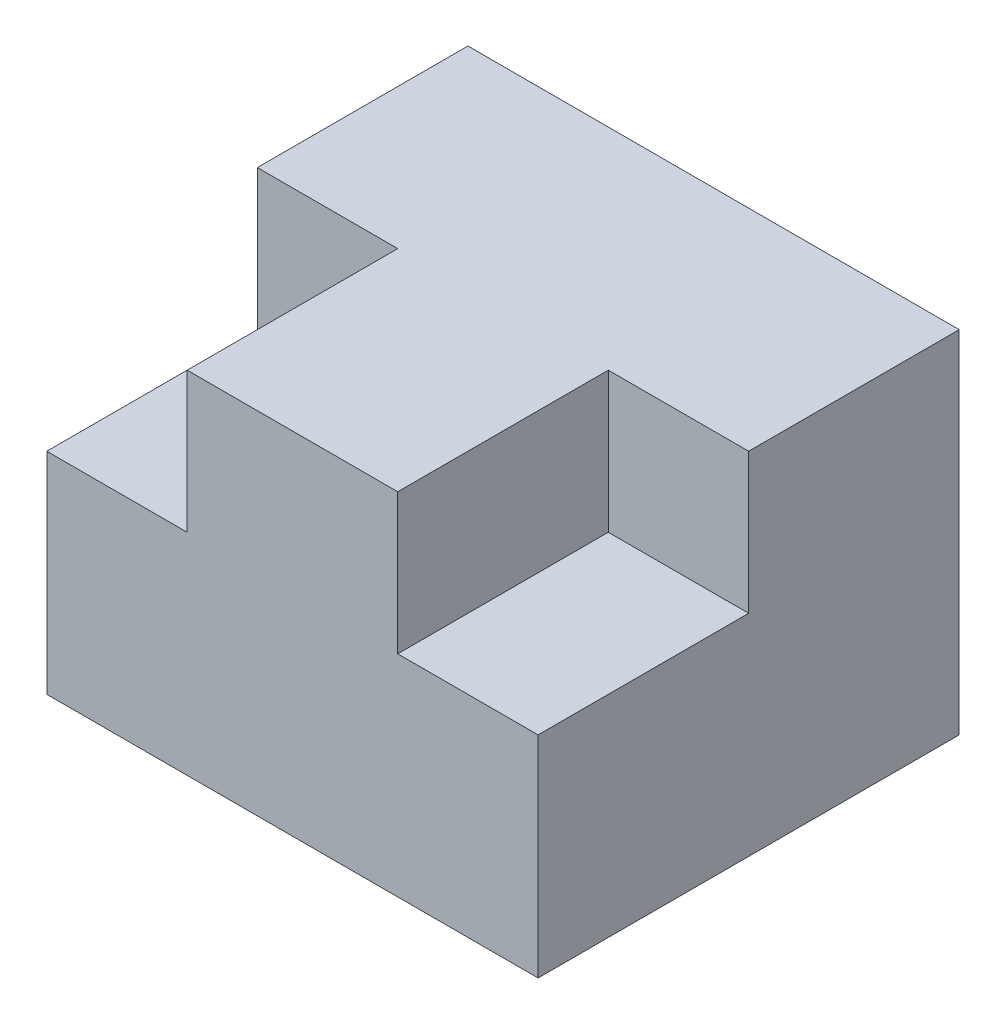
SolidWorks part; units mm, degrees
ref_plane "Front Plane" through (0, 0, 0) normal (0, 0, 1) x (1, 0, 0)
ref_plane "Top Plane" through (0, 0, 0) normal (0, 1, 0) x (1, 0, 0)
ref_plane "Right Plane" through (0, 0, 0) normal (1, 0, 0) x (0, 0, -1)
sketch "Sketch1" plane through (0, 0, 0) normal (0, 0, 1) x (1, 0, 0)
  line L0 (-17.5, 0) -> (17.5, 0)
  line L1 (17.5, 0) -> (17.5, 15)
  line L2 (17.5, 15) -> (7.5, 15)
  line L3 (7.5, 15) -> (7.5, 25)
  line L4 (7.5, 25) -> (-7.5, 25)
  line L5 (-7.5, 25) -> (-7.5, 15)
  line L6 (-7.5, 15) -> (-17.5, 15)
  line L7 (-17.5, 15) -> (-17.5, 0)
  point P4 (0, 0)
  dimension "D1" = 15
  dimension "35" = 35
  dimension "D2" = 10
  dimension "D3" = 10
  dimension "D4" = 10
  dimension "D5" = 10
extrude "Boss-Extrude1" add sketch "Sketch1" along normal blind 15
sketch "Sketch2" plane through (0, 0, 0) normal (0, 0, -1) x (-1, 0, 0)
  line L1 (-17.5, 0) -> (17.5, 0)
  line L2 (-17.5, 0) -> (-17.5, 25)
  line L3 (-17.5, 25) -> (17.5, 25)
  line L4 (17.5, 0) -> (17.5, 25)
  dimension "D1" = 25
  dimension "D2" = 35
extrude "Boss-Extrude2" add sketch "Sketch2" along normal blind 15
